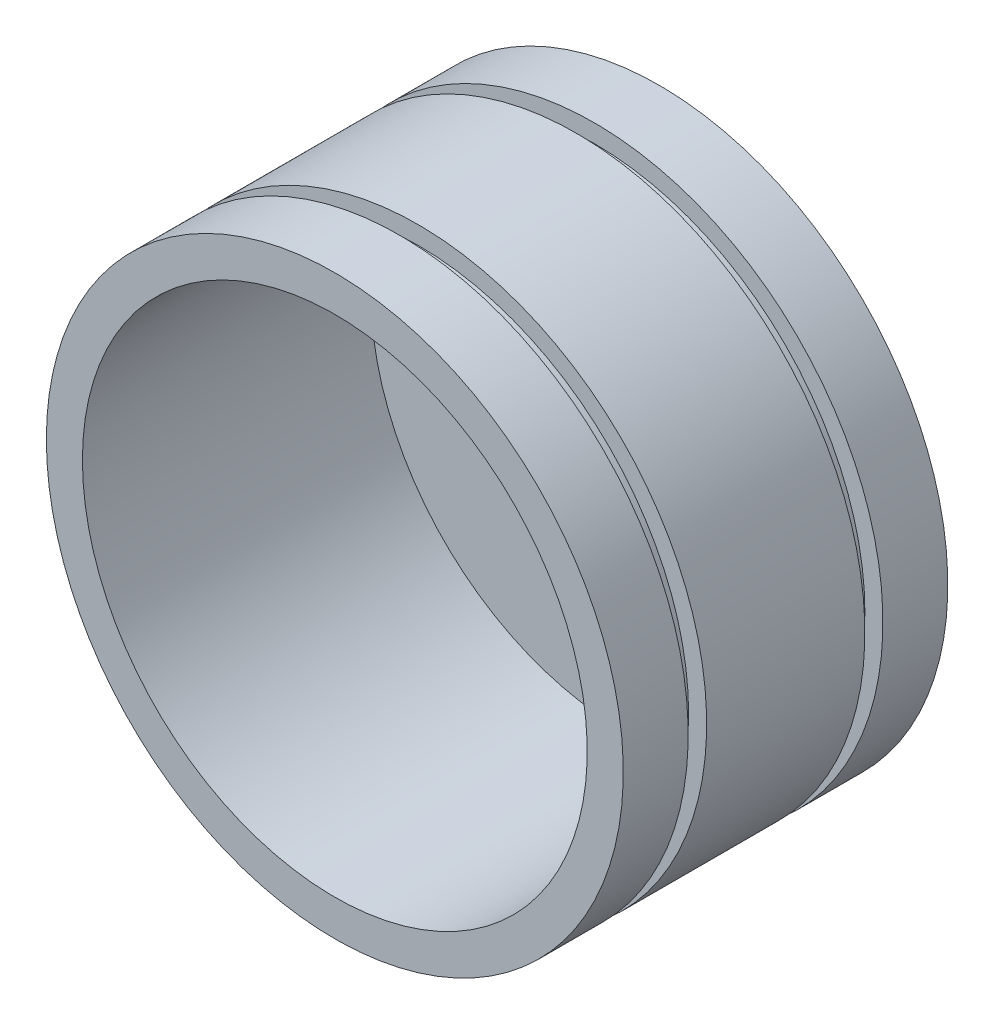
SolidWorks part; units mm, degrees
material "6061 Alloy"
ref_plane "Front Plane" through (0, 0, 0) normal (0, 0, 1) x (1, 0, 0)
ref_plane "Top Plane" through (0, 0, 0) normal (0, 1, 0) x (1, 0, 0)
ref_plane "Right Plane" through (0, 0, 0) normal (1, 0, 0) x (0, 0, -1)
sketch "Sketch2" plane through (0, 0, 0) normal (0, 1, 0) x (1, 0, 0)
  line L0 (-16.3518, 17.2972) -> (-22.7018, 17.2972)
  line L1 (-22.7018, 17.2972) -> (-22.7018, 28.7272)
  line L2 (-22.7018, 28.7272) -> (-19.5268, 28.7272)
  line L3 (-19.5268, 28.7272) -> (-19.5268, 31.9784)
  line L4 (-19.5268, 31.9784) -> (-22.7018, 31.9784)
  line L5 (-22.7018, 31.9784) -> (-22.7018, 59.8422)
  line L6 (-22.7018, 59.8422) -> (-19.5268, 59.8422)
  line L7 (-19.5268, 59.8422) -> (-19.5268, 63.0172)
  line L8 (-19.5268, 63.0172) -> (-22.7018, 63.0172)
  line L9 (-22.7018, 63.0172) -> (-22.7018, 74.4472)
  line L23 (-16.3518, 68.0972) -> (-16.3518, 17.2972)
  line L24 (28.0982, 74.4472) -> (28.0982, 0.1208) construction
  line L25 (-22.7018, 74.4472) -> (28.0982, 74.4472)
  line L26 (-16.3518, 68.0972) -> (28.0982, 68.0972)
  line L27 (28.0982, 74.4472) -> (28.0982, 68.0972)
  dimension "D2" = 3.2512
  dimension "D3" = 3.175
  dimension "D4" = 3.175
  dimension "D5" = 3.175
  dimension "D6" = 3.175
  dimension "D7" = 3.175
  dimension "D8" = 50.8
  dimension "D9" = 57.15
  dimension "D11" = 6.35
  dimension "D13" = 11.43
  dimension "D14" = 11.43
  dimension "D15" = 6.35
revolve "Revolve1" add sketch "Sketch2" angle 360 about L24
sketch "Sketch3" plane through (0, 0, -68.0972) normal (0, 0, 1) x (1, 0, 0)
  circle A0 centre (28.0982, 0) radius 3.81
  dimension "D1" = 7.62
extrude "Cut-Extrude1" cut sketch "Sketch3" against normal through all
